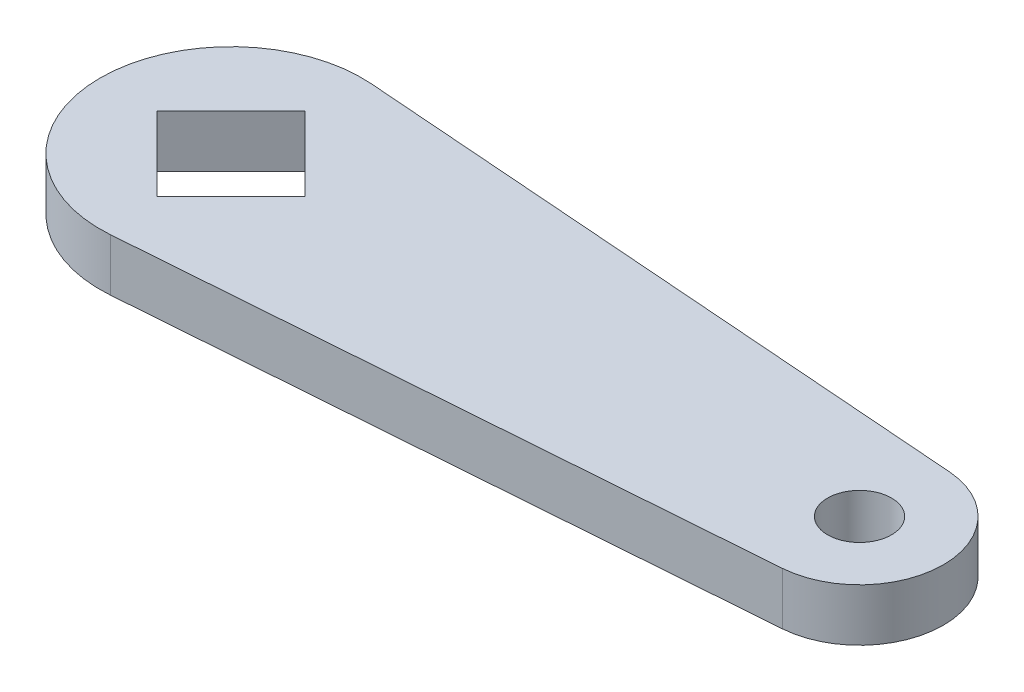
SolidWorks part; units mm, degrees
ref_plane "前视基准面" through (0, 0, 0) normal (0, 0, 1) x (1, 0, 0)
ref_plane "上视基准面" through (0, 0, 0) normal (0, 1, 0) x (1, 0, 0)
ref_plane "右视基准面" through (0, 0, 0) normal (1, 0, 0) x (0, 0, -1)
sketch "草图1" plane through (0, 0, 0) normal (0, 1, 0) x (1, 0, 0)
  line L0 (-55, 0) -> (55, 0) construction
  line L1 (0.9375, -12.4648) -> (60.6, -7.9775)
  line L2 (0.9375, 12.4648) -> (60.6, 7.9775)
  line L3 (-7.0711, 0) -> (0, 7.0711)
  line L4 (-7.0711, 0) -> (0, -7.0711)
  line L5 (0, 7.0711) -> (7.0711, 0)
  line L6 (0, -7.0711) -> (7.0711, 0)
  line L7 (-7.0711, 0) -> (7.0711, 0) construction
  line L8 (0, 7.0711) -> (0, -7.0711) construction
  line L9 (0, -55) -> (0, 55) construction
  circle A0 centre (0, 0) radius 12.5
  circle A1 centre (60, 0) radius 8
  circle A2 centre (60, 0) radius 3.05
  dimension "D1" = 25
  dimension "D2" = 16
  dimension "D5" = 6.1
  dimension "D3" = 60
  dimension "D4" = 10
extrude "凸台-拉伸1" add sketch "草图1" along normal blind 5 contours A1 L2 A0 L1 | A0 L6 L4 L3 L5 | A1 A2
